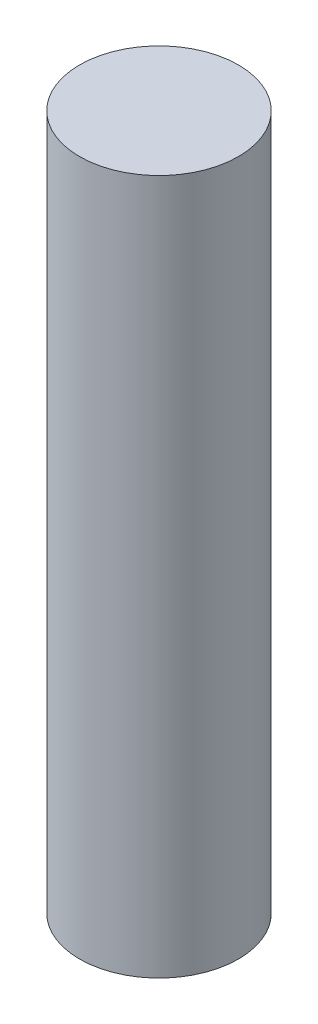
SolidWorks part; units mm, degrees
ref_plane "Front" through (0, 0, 0) normal (0, 0, 1) x (1, 0, 0)
ref_plane "Top" through (0, 0, 0) normal (0, 1, 0) x (1, 0, 0)
ref_plane "Right" through (0, 0, 0) normal (1, 0, 0) x (0, 0, -1)
sketch "Esquisse1" plane through (0, 0, 0) normal (0, 1, 0) x (1, 0, 0)
  circle A0 centre (0, 0) radius 4
  dimension "D1" = 8
extrude "Boss.-Extru.1" add sketch "Esquisse1" along normal blind 35
